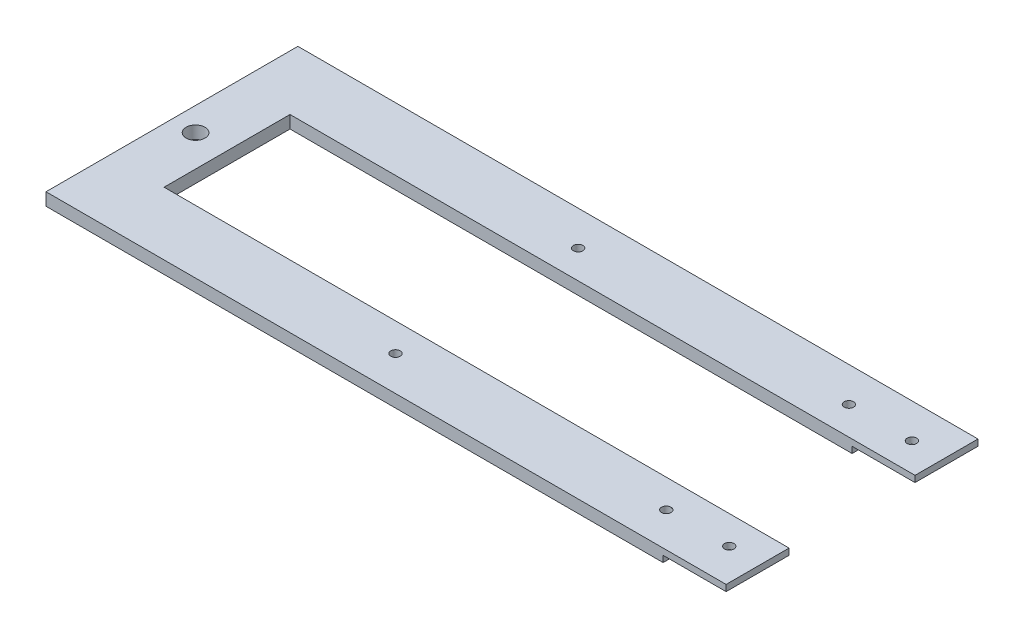
SolidWorks part; units mm, degrees
ref_plane "Front Plane" through (0, 0, 0) normal (0, 0, 1) x (1, 0, 0)
ref_plane "Top Plane" through (0, 0, 0) normal (0, 1, 0) x (1, 0, 0)
ref_plane "Right Plane" through (0, 0, 0) normal (1, 0, 0) x (0, 0, -1)
sketch "Sketch1" plane through (0, 0, 0) normal (0, 1, 0) x (1, 0, 0)
  line L0 (0, -40) -> (0, 40)
  line L1 (0, 40) -> (196, 40)
  line L2 (196, 40) -> (196, 20)
  line L3 (-190.8824, 0) -> (429.1176, 0) construction
  line L4 (196, 20) -> (17.5, 20)
  line L5 (17.5, 20) -> (17.5, -20)
  line L6 (17.5, 0) -> (0, 0)
  line L7 (196, -20) -> (17.5, -20)
  line L8 (196, -40) -> (196, -20)
  line L9 (0, -40) -> (196, -40)
  circle A0 centre (7.5, 0) radius 3
  circle A1 centre (100, 29) radius 1.5
  circle A2 centre (186, 29) radius 1.5
  circle A3 centre (186, -29) radius 1.5
  circle A4 centre (100, -29) radius 1.5
  dimension "D5" = 0
  dimension "D6" = 6
  dimension "D7" = 3
  dimension "D8" = 3
  dimension "D9" = 86
  dimension "D10" = 29
  dimension "D11" = 10
  dimension "D13" = 29
  dimension "D14" = 58
  dimension "D1" = 40
  dimension "D2" = 17.5
  dimension "D3" = 20
  dimension "D4" = 196
  dimension "D12" = 7.5
extrude "Boss-Extrude1" add sketch "Sketch1" along normal blind 4 contours A0 L6 L0 L9 L8 L7 L5 A3 A4 | A0 L6 L5 L4 L2 L1 L0 A2 A1
sketch "Sketch2" plane through (196, 0, 0) normal (1, 0, 0) x (0, 0, -1)
  line L0 (40, 4) -> (40, 0) construction
  line L1 (20, 4) -> (40, 4)
  line L2 (20, 4) -> (20, 2)
  line L3 (20, 2) -> (40, 2)
  line L4 (40, 4) -> (40, 2)
  line L5 (0, 0) -> (0, 24.9083) construction
  line L6 (-20, 2) -> (-40, 2)
  line L7 (-40, 4) -> (-40, 2)
  line L8 (-20, 4) -> (-40, 4)
  line L9 (-20, 4) -> (-20, 2)
extrude "Boss-Extrude2" add sketch "Sketch2" along normal blind 20
sketch "Sketch4" plane through (0, 4, 0) normal (0, 1, 0) x (1, 0, 0)
  line L0 (216, 20) -> (17.5, 20) construction
  line L2 (196, 48.7371) -> (196, -44.997) construction
  line L3 (216, 40) -> (216, 20) construction
  circle A0 centre (186, 29) radius 1.5
  circle A1 centre (186, -29) radius 1.5
  circle A2 centre (206, 29) radius 1.5
  circle A3 centre (206, -29) radius 1.5
  dimension "D2" = 3
  dimension "D3" = 3
  dimension "D4" = 10
  dimension "D1" = 9
extrude "Cut-Extrude1" cut sketch "Sketch4" against normal blind 10
